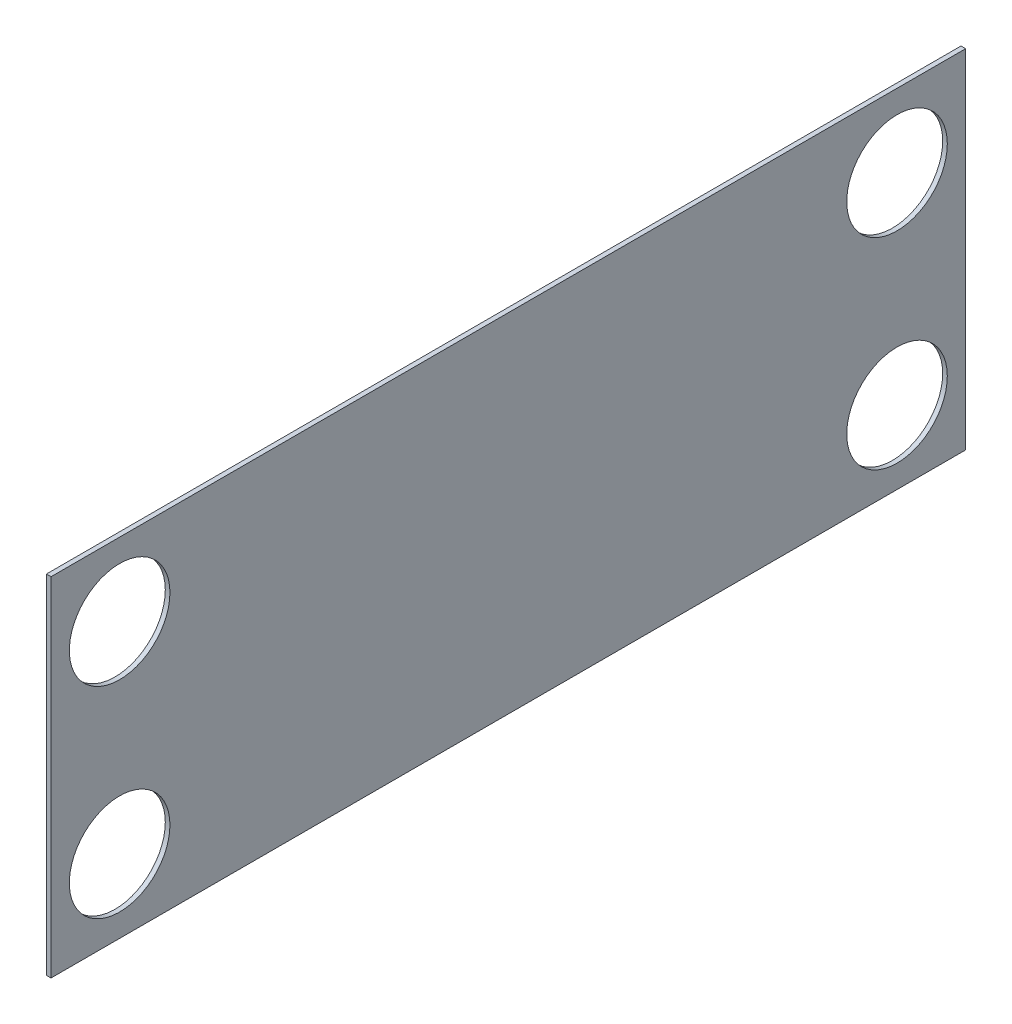
SolidWorks part; units mm, degrees
material "Low Carbon Steel"
ref_plane "Front Plane" through (0, 0, 0) normal (0, 0, 1) x (1, 0, 0)
ref_plane "Top Plane" through (0, 0, 0) normal (0, 1, 0) x (1, 0, 0)
ref_plane "Right Plane" through (0, 0, 0) normal (1, 0, 0) x (0, 0, -1)
sketch "Sketch1" plane through (0, 0, 0) normal (1, 0, 0) x (0, 0, -1)
  line L0 (50, 19) -> (-50, -19) construction
  line L1 (-50, 19) -> (50, 19)
  line L2 (-50, 19) -> (-50, -19)
  line L3 (-50, -19) -> (50, -19)
  line L4 (50, 19) -> (50, -19)
  dimension "D1" = 100
  dimension "D2" = 38
extrude "Boss-Extrude1" add sketch "Sketch1" along normal blind 0.508
hole_wizard "M10 Clearance Hole1" positions "Sketch2" profile "Sketch3" hole size "M10" standard "Peddi DIN" end condition through all
sketch "Sketch2" plane through (0.508, 0, 0) normal (1, 0, 0) x (0, 0, -1)
  line L0 (42.5, 11) -> (42.5, -11) construction
  line L1 (42.5, -11) -> (-42.5, 11) construction
  line L2 (-42.5, 11) -> (-42.5, -11) construction
  line L3 (-42.5, -11) -> (42.5, -11) construction
  point P0 (-42.5, 11)
  point P2 (-42.5, -11)
  point P4 (42.5, 11)
  point P6 (42.5, -11)
  dimension "D1" = 22
  dimension "D2" = 85
sketch "Sketch3" plane through (0.508, 11, 42.5) normal (0, 1, 0) x (0, 0, -1)
  line L0 (0, 0) -> (0, 0.508)
  line L1 (0, 0.508) -> (5.5, 0.508)
  line L2 (5.5, 0.508) -> (5.5, 0)
  line L5 (5.5, 0) -> (0, 0)
  line L11 (0, -6.35) -> (0, 107.95) construction
  dimension "Thru Hole Dia." = 11
  dimension "Thru Hole Depth" = 0.508
other "Freeze***"
